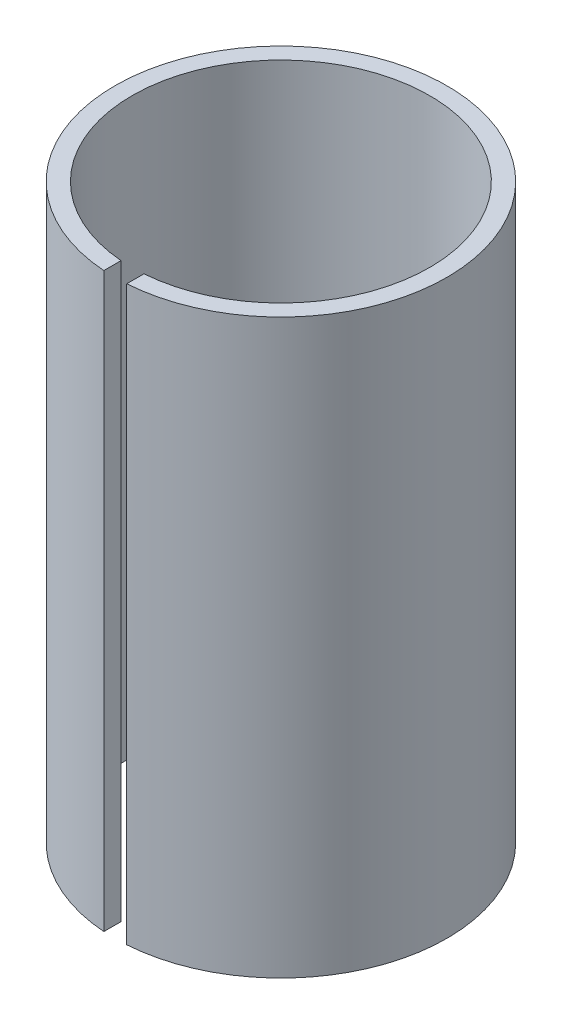
SolidWorks part; units mm, degrees
material "Rubber"
ref_plane "Front Plane" through (0, 0, 0) normal (0, 0, 1) x (1, 0, 0)
ref_plane "Top Plane" through (0, 0, 0) normal (0, 1, 0) x (1, 0, 0)
ref_plane "Right Plane" through (0, 0, 0) normal (1, 0, 0) x (0, 0, -1)
sketch "Sketch1" plane through (0, 0, 0) normal (0, 1, 0) x (1, 0, 0)
  line L0 (-1, -12.9615) -> (-1, -14.4655)
  line L1 (1, -12.9615) -> (1, -14.4655)
  line L2 (0, 13) -> (0, -13) construction
  circle A0 centre (0, 0) radius 14.5
  circle A1 centre (0, 0) radius 13
  dimension "D1" = 29
  dimension "D2" = 26
  dimension "D3" = 1
  dimension "D4" = 1
extrude "Boss-Extrude1" add sketch "Sketch1" along normal blind 50 contours A1 L1 A0 L0
